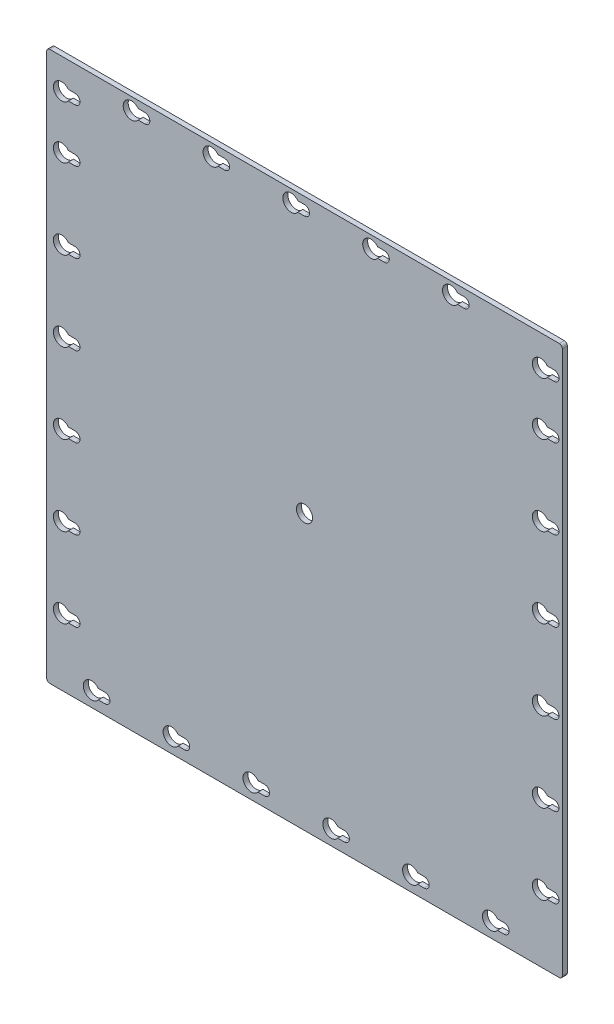
SolidWorks part; units mm, degrees
material "6061 Alloy"
ref_plane "Front Plane" through (0, 0, 0) normal (0, 0, 1) x (1, 0, 0)
ref_plane "Top Plane" through (0, 0, 0) normal (0, 1, 0) x (1, 0, 0)
ref_plane "Right Plane" through (0, 0, 0) normal (1, 0, 0) x (0, 0, -1)
sketch "Sketch1" plane through (0, 0, 0) normal (0, 0, 1) x (1, 0, 0)
  line L0 (0, 0) -> (0, -174.745)
  line L3 (0, -174.745) -> (165.1, -174.745)
  line L5 (0, 0) -> (165.1, 0)
  line L6 (165.1, -174.745) -> (165.1, 0)
  line L7 (82.55, 0) -> (82.55, -174.745) construction
  line L8 (31.75, -2.2625) -> (29.6344, -2.2625)
  line L9 (31.75, -5.4375) -> (29.6344, -5.4375)
  line L10 (9.525, -24.9325) -> (7.4094, -24.9325)
  line L11 (9.525, -28.1075) -> (7.4094, -28.1075)
  line L12 (161.925, -24.9325) -> (159.8094, -24.9325)
  line L13 (161.925, -28.1075) -> (159.8094, -28.1075)
  line L14 (57.15, -2.2625) -> (55.0344, -2.2625)
  line L15 (57.15, -5.4375) -> (55.0344, -5.4375)
  line L16 (82.55, -2.2625) -> (80.4344, -2.2625)
  line L17 (82.55, -5.4375) -> (80.4344, -5.4375)
  line L18 (107.95, -2.2625) -> (105.8344, -2.2625)
  line L19 (107.95, -5.4375) -> (105.8344, -5.4375)
  line L20 (133.35, -2.2625) -> (131.2344, -2.2625)
  line L21 (133.35, -5.4375) -> (131.2344, -5.4375)
  line L22 (9.525, -50.3325) -> (7.4094, -50.3325)
  line L23 (9.525, -53.5075) -> (7.4094, -53.5075)
  line L24 (161.925, -50.3325) -> (159.8094, -50.3325)
  line L25 (161.925, -53.5075) -> (159.8094, -53.5075)
  line L26 (9.525, -75.7325) -> (7.4094, -75.7325)
  line L27 (9.525, -78.9075) -> (7.4094, -78.9075)
  line L28 (161.925, -75.7325) -> (159.8094, -75.7325)
  line L29 (161.925, -78.9075) -> (159.8094, -78.9075)
  line L30 (9.525, -101.1325) -> (7.4094, -101.1325)
  line L31 (9.525, -104.3075) -> (7.4094, -104.3075)
  line L32 (161.925, -101.1325) -> (159.8094, -101.1325)
  line L33 (161.925, -104.3075) -> (159.8094, -104.3075)
  line L34 (9.525, -126.5325) -> (7.4094, -126.5325)
  line L35 (9.525, -129.7075) -> (7.4094, -129.7075)
  line L36 (161.925, -126.5325) -> (159.8094, -126.5325)
  line L37 (161.925, -129.7075) -> (159.8094, -129.7075)
  line L38 (9.525, -151.9325) -> (7.4094, -151.9325)
  line L39 (9.525, -155.1075) -> (7.4094, -155.1075)
  line L40 (161.925, -151.9325) -> (159.8094, -151.9325)
  line L41 (161.925, -155.1075) -> (159.8094, -155.1075)
  line L42 (19.05, -168.395) -> (16.9344, -168.395)
  line L43 (19.05, -171.57) -> (16.9344, -171.57)
  line L44 (44.45, -168.395) -> (42.3344, -168.395)
  line L45 (44.45, -171.57) -> (42.3344, -171.57)
  line L46 (69.85, -168.395) -> (67.7344, -168.395)
  line L47 (69.85, -171.57) -> (67.7344, -171.57)
  line L48 (95.25, -168.395) -> (93.1344, -168.395)
  line L49 (95.25, -171.57) -> (93.1344, -171.57)
  line L50 (120.65, -168.395) -> (118.5344, -168.395)
  line L51 (120.65, -171.57) -> (118.5344, -171.57)
  line L52 (146.05, -168.395) -> (143.9344, -168.395)
  line L53 (146.05, -171.57) -> (143.9344, -171.57)
  line L54 (0.5, 0) -> (0.5, -174.745)
  line L55 (164.6, -174.745) -> (164.6, 0)
  line L56 (0.5, -174.745) -> (164.6, -174.745)
  line L57 (9.525, -8.1) -> (7.4094, -8.1)
  line L58 (9.525, -11.275) -> (7.4094, -11.275)
  line L59 (161.925, -8.1) -> (159.8094, -8.1)
  line L60 (161.925, -11.275) -> (159.8094, -11.275)
  circle A41 centre (9.525, -153.52) radius 1.5875
  circle A42 centre (19.05, -169.9825) radius 1.5875
  circle A43 centre (9.525, -128.12) radius 1.5875
  circle A44 centre (9.525, -102.72) radius 1.5875
  circle A45 centre (9.525, -77.32) radius 1.5875
  circle A46 centre (9.525, -51.92) radius 1.5875
  circle A47 centre (9.525, -26.52) radius 1.5875
  circle A49 centre (44.45, -169.9825) radius 1.5875
  circle A50 centre (69.85, -169.9825) radius 1.5875
  circle A51 centre (95.25, -169.9825) radius 1.5875
  circle A52 centre (120.65, -169.9825) radius 1.5875
  circle A68 centre (146.05, -169.9825) radius 1.5875
  circle A69 centre (107.95, -3.85) radius 1.5875
  circle A70 centre (82.55, -3.85) radius 1.5875
  circle A71 centre (57.15, -3.85) radius 1.5875
  circle A72 centre (9.525, -1.12) radius 1.5875 [skipped]
  circle A73 centre (133.35, -3.85) radius 1.5875
  circle A74 centre (31.75, -3.85) radius 1.5875
  circle A75 centre (161.925, -26.52) radius 1.5875
  circle A76 centre (161.925, -51.92) radius 1.5875
  circle A77 centre (161.925, -77.32) radius 1.5875
  circle A78 centre (161.925, -102.72) radius 1.5875
  circle A79 centre (161.925, -128.12) radius 1.5875
  circle A80 centre (161.925, -153.52) radius 1.5875
  circle A81 centre (27.5125, -3.85) radius 2.65
  circle A83 centre (5.2875, -26.52) radius 2.65
  circle A84 centre (157.6875, -26.52) radius 2.65
  circle A85 centre (52.9125, -3.85) radius 2.65
  circle A86 centre (78.3125, -3.85) radius 2.65
  circle A87 centre (103.7125, -3.85) radius 2.65
  circle A88 centre (129.1125, -3.85) radius 2.65
  circle A89 centre (5.2875, -51.92) radius 2.65
  circle A90 centre (157.6875, -51.92) radius 2.65
  circle A91 centre (5.2875, -77.32) radius 2.65
  circle A92 centre (157.6875, -77.32) radius 2.65
  circle A93 centre (5.2875, -102.72) radius 2.65
  circle A94 centre (157.6875, -102.72) radius 2.65
  circle A95 centre (5.2875, -128.12) radius 2.65
  circle A96 centre (157.6875, -128.12) radius 2.65
  circle A97 centre (5.2875, -153.52) radius 2.65
  circle A98 centre (157.6875, -153.52) radius 2.65
  circle A99 centre (14.8125, -169.9825) radius 2.65
  circle A100 centre (40.2125, -169.9825) radius 2.65
  circle A101 centre (65.6125, -169.9825) radius 2.65
  circle A102 centre (91.0125, -169.9825) radius 2.65
  circle A103 centre (116.4125, -169.9825) radius 2.65
  circle A104 centre (141.8125, -169.9825) radius 2.65
  circle A105 centre (82.55, -87.3725) radius 2.5527
  circle A107 centre (9.525, -9.6875) radius 1.5875
  circle A108 centre (5.2875, -9.6875) radius 2.65
  circle A109 centre (161.925, -9.6875) radius 1.5875
  circle A110 centre (157.6875, -9.6875) radius 2.65
  dimension "D3" = 3.175
  dimension "D8" = 3.175
  dimension "D21" = 5.3
  dimension "D31" = 5.1054
  dimension "D33" = 5.3
  dimension "D1" = 165.1
  dimension "D2" = 174.745
  dimension "D5" = 9.525
  dimension "D4" = 21.225
  dimension "D6" = 19.05
  dimension "D7" = 4.7625
  dimension "D9" = 25.4
  dimension "D10" = 25.4
  dimension "D15" = 25.4
  dimension "D12" = 3.85
  dimension "D13" = 31.75
  dimension "D17" = 31.75
  dimension "D18" = 3.175
  dimension "D20" = 25.4
  dimension "D23" = 25.4
  dimension "D25" = 25.4
  dimension "D27" = 25.4
  dimension "D28" = 0.5
  dimension "D29" = 0.5
  dimension "D30" = 87.3725
  dimension "D34" = 16.8325
  dimension "D35" = 5.8375
  dimension "D11" = 7
  dimension "D14" = 5
  dimension "D16" = 5
  dimension "D19" = 6
  dimension "D22" = 5
  dimension "D24" = 6
  dimension "D26" = 6
extrude "Boss-Extrude1" add sketch "Sketch1" along normal blind 1.5875 contours L7 L5 L0 L3 A50 A41 A42 A43 A44 A45 A46 A47 A73 A49 | L5 L7 A70 A105 L56 L55 A84 L12 A75 L13 A87 L18 A69 L19 A88 L20 A73 L21 A90 L24 A76 L25 A92 L28 A77 L29 A94 L32 A78 L33 A96 L36 A79 L37 A98 L40 A80 L41 A102 L48
fillet "Fillet1" radius 1 4 edges at (164.6, 0, 0.7937) (164.6, -174.745, 0.7937) (0.5, -174.745, 0.7937) (0.5, 0, 0.7937)
equation "\"D8@Sketch1\"=\"D3@Sketch1\""
equation "\"D29@Sketch1\"=\"D28@Sketch1\""
equation "\"D30@Sketch1\"=\"D2@Sketch1\"/2"
